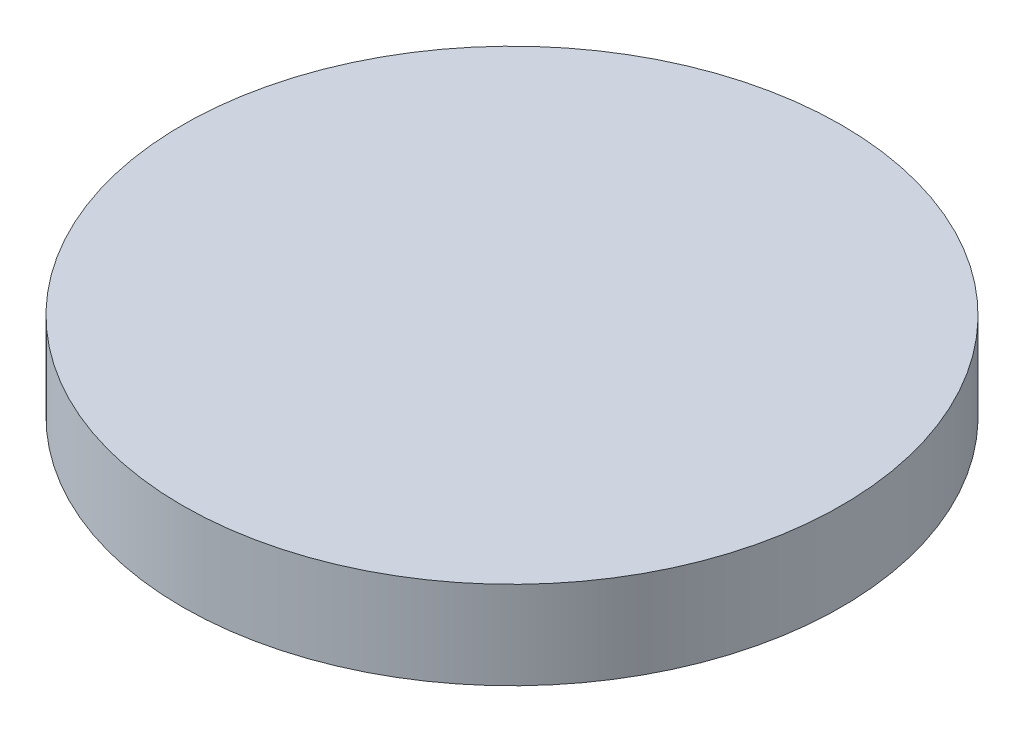
SolidWorks part; units mm, degrees
ref_plane "Front Plane" through (0, 0, 0) normal (0, 0, 1) x (1, 0, 0)
ref_plane "Top Plane" through (0, 0, 0) normal (0, 1, 0) x (1, 0, 0)
ref_plane "Right Plane" through (0, 0, 0) normal (1, 0, 0) x (0, 0, -1)
sketch "Sketch1" plane through (0, 0, 0) normal (0, 1, 0) x (1, 0, 0)
  circle A0 centre (-59.3034, 6.5784) radius 23.8125
  dimension "D1" = 47.625
extrude "Boss-Extrude1" add sketch "Sketch1" along normal blind 6.35
